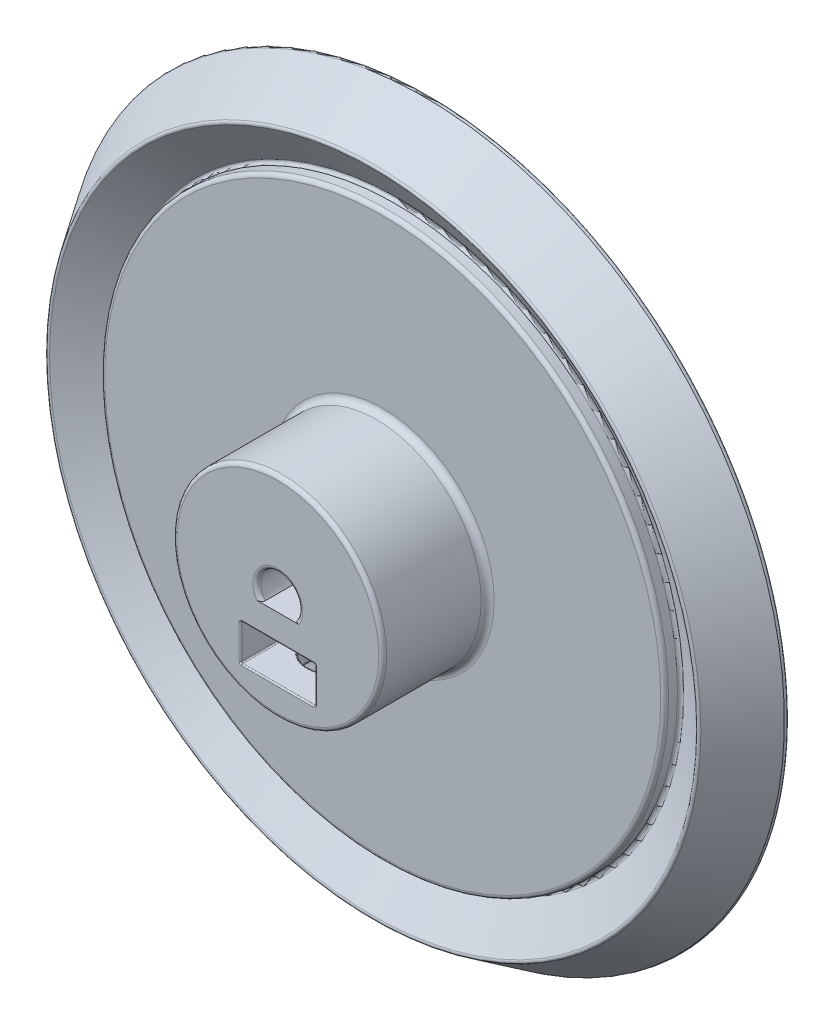
SolidWorks part; units mm, degrees
ref_plane "Front Plane" through (0, 0, 0) normal (0, 0, 1) x (1, 0, 0)
ref_plane "Top Plane" through (0, 0, 0) normal (0, 1, 0) x (1, 0, 0)
ref_plane "Right Plane" through (0, 0, 0) normal (1, 0, 0) x (0, 0, -1)
sketch "Sketch1" plane through (0, 0, 0) normal (0, 0, 1) x (1, 0, 0)
  circle A0 centre (0, 0) radius 25
  dimension "D1" = 50
extrude "Boss-Extrude1" add sketch "Sketch1" along normal mid plane 7.7
sketch "Sketch2" plane through (0, 0, 0) normal (0, 1, 0) x (1, 0, 0)
  line L1 (25, 0) -> (23.8588, 0) construction
  line L3 (21.5, 2.5) -> (27.9368, 2.5)
  line L4 (27.9368, 2.5) -> (27.9368, -2.5)
  line L5 (21.5, 2.5) -> (21.5, 7.2558)
  line L6 (21.5, 7.2558) -> (28.6124, 7.2558)
  line L7 (28.6124, 7.2558) -> (28.6124, -7.2558)
  line L8 (21.5, -7.2558) -> (28.6124, -7.2558)
  line L9 (21.5, -2.5) -> (21.5, -7.2558)
  line L10 (21.5, -2.5) -> (27.9368, -2.5)
  line L12 (25, -3.85) -> (25, 3.85) construction
  point P10 (28.6124, 0)
  point P13 (27.9368, 0)
  dimension "D1" = 5
  dimension "D2" = 3.5
sweep "Cut-Sweep1" cut profiles "Sketch2" path edge at (25, 0, -3.85)
sketch "Sketch3" plane through (0, 0, 0) normal (0, 1, 0) x (1, 0, 0)
  line L0 (-27.5, 0) -> (27.5, 0) construction
  line L1 (28.85, 0) -> (28.85, -1.1107) construction
  circle A0 centre (26.25, 0) radius 2.6
  dimension "D2" = 5.2
  dimension "D1" = 28.85
sketch "Sketch4" plane through (0, 0, 3.85) normal (0, 0, 1) x (1, 0, 0)
  circle A0 centre (0, 0) radius 8
  dimension "D1" = 16
extrude "Boss-Extrude2" add sketch "Sketch4" along normal blind 8
sketch "Sketch5" plane through (0, 0, 11.85) normal (0, 0, 1) x (1, 0, 0)
  line L1 (-1.249, -1) -> (1.249, -1)
  arc A0 (1.249, -1) -> (-1.249, -1) centre (0, 0) ccw
  dimension "D1" = 3.2
  dimension "D2" = 1
extrude "Cut-Extrude1" cut sketch "Sketch5" against normal blind 9
sketch "Sketch6" plane through (0, 0, 0) normal (0, 1, 0) x (1, 0, 0)
  line L0 (0, -55) -> (0, 55) construction
  line L1 (-8, -11.85) -> (8, -11.85) construction
  circle A0 centre (0, -7.55) radius 2
  dimension "D1" = 4
  dimension "D2" = 4.3
extrude "Cut-Extrude2" cut sketch "Sketch6" against normal through all
fillet "Fillet1" radius 0.5 1 edges at (8, 0, 3.85)
sketch "Sketch7" plane through (0, 0, -3.85) normal (0, 0, -1) x (-1, 0, 0)
  circle A0 centre (0, 0) radius 31.3112
  dimension "D1" = 62.6225
sketch "Sketch10" plane through (0, 0, 0) normal (1, 0, 0) x (0, 0, -1)
  line L0 (-2.5, 21.5) -> (-4.7018, 24.8394)
  line L1 (-4.7018, 24.8394) -> (-0.5275, 27.5917)
  line L2 (-0.5275, 27.5917) -> (2.5, 23)
  line L3 (3.85, 21.5) -> (2.5, 21.5) construction
  line L4 (2.5, -25) -> (2.5, 25) construction
  line L7 (5.9793, 25.4496) -> (0.9257, 30.4705)
  line L8 (0.9257, 30.4705) -> (-10.1067, 28.9854)
  line L9 (-10.1067, 28.9854) -> (-7.1437, 23.3484)
  line L10 (-7.1437, 23.3484) -> (-2.5, 21.5)
  line L11 (0, 0) -> (8.9282, 0) construction
  line L12 (2.5084, 21.5) -> (2.5242, 21.5) construction
  line L13 (-2.5, 25) -> (-2.5, -25) construction
  line L14 (2.5, 23) -> (5.9793, 25.4496)
  dimension "D1" = 5
  dimension "D2" = 4
  dimension "D3" = 90
  dimension "D4" = 90
  dimension "D5" = 1.5
revolve "Cut-Revolve1" cut sketch "Sketch10" angle 360 about L11
sketch "Sketch11" plane through (0, 0, 0) normal (1, 0, 0) x (0, 0, -1)
  line L0 (2.5, 23) -> (2.5, 21.5)
  line L1 (2.5, 21.5) -> (-2.5, 21.5)
  line L2 (0, 0) -> (6.6681, 0) construction
  line L8 (-2.5, 21.5) -> (-4.7018, 24.8394)
  line L9 (-4.7018, 24.8394) -> (-0.5275, 27.5917)
  line L10 (-0.5275, 27.5917) -> (2.5, 23)
  line L11 (2.5, 23) -> (5.9793, 25.4496)
  line L12 (5.9793, 25.4496) -> (0.9257, 30.4705)
  line L13 (0.9257, 30.4705) -> (-10.1067, 28.9854)
  line L14 (-10.1067, 28.9854) -> (-7.1437, 23.3484)
  line L15 (-7.1437, 23.3484) -> (-2.5, 21.5)
  line L16 (-2.5, 21.5) -> (-4.7018, 24.8394)
  line L17 (-4.7018, 24.8394) -> (-0.5275, 27.5917)
  line L18 (-0.5275, 27.5917) -> (2.5, 23)
  dimension "D1" = 0
revolve "Revolve3" add sketch "Sketch11" angle 360 about L2
fillet "Fillet2" radius 0.3 1 edges at (8, 0, 11.85)
fillet "Fillet3" radius 0.3 1 edges at (-0.3912, -7.9904, 5.5886)
fillet "Fillet4" radius 0.3 1 edges at (0, 1.6, 11.85)
fillet "Fillet5" radius 0.3 3 edges at (21.5, 0, -3.85) (21.5, 0, -2.5) (21.5, 0, 3.85)
sketch "Sketch8" plane through (0, 0, 11.85) normal (0, 0, 1) x (1, 0, 0)
  line L1 (-2.85, -3) -> (2.85, -3)
  line L2 (-2.85, -3) -> (-2.85, -5.8)
  line L3 (-2.85, -5.8) -> (2.85, -5.8)
  line L4 (2.85, -3) -> (2.85, -5.8)
  point P4 (0, -3)
  dimension "D1" = 2.8
  dimension "D2" = 5.7
  dimension "D3" = 3
extrude "Cut-Extrude3" cut sketch "Sketch8" against normal blind 9
fillet "Fillet6" radius 0.1 14 edges at (0, -3, 9.55) (0, -3, 11.85) (0, -5.8, 5.55) (0, -5.8, 11.85) (-2.85, -3, 7.35) (-2.85, -5.8, 7.35) (-2.85, -4.4, 11.85) (2.85, -5.8, 7.35) (2.85, -3, 7.35) (2.85, -4.4, 11.85) (0, -3, 2.85) (2.85, -4.4, 2.85) (0, -5.8, 2.85) (-2.85, -4.4, 2.85)
fillet "Fillet7" radius 0.2 4 edges at (23, 0, -2.5) (27.5917, 0, 0.5275) (24.8394, 0, 4.7018) (21.5, 0, 2.5)
